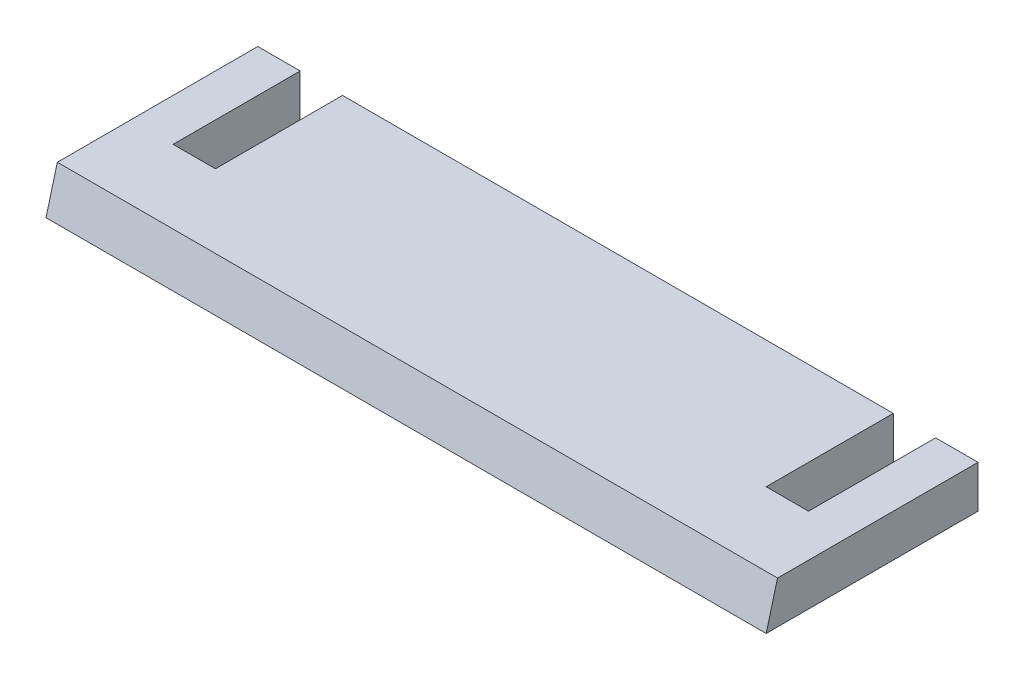
SolidWorks part; units mm, degrees
ref_plane "Front Plane" through (0, 0, 0) normal (0, 0, 1) x (1, 0, 0)
ref_plane "Top Plane" through (0, 0, 0) normal (0, 1, 0) x (1, 0, 0)
ref_plane "Right Plane" through (0, 0, 0) normal (1, 0, 0) x (0, 0, -1)
sketch "Sketch1" plane through (0, 0, 0) normal (0, 1, 0) x (1, 0, 0)
  line L0 (-75, 25) -> (-75, -5)
  line L1 (-85, -25) -> (85, -25)
  line L2 (-85, -25) -> (-85, 25)
  line L3 (-85, 25) -> (-75, 25)
  line L4 (85, -25) -> (85, 25)
  line L5 (-85, -25) -> (85, 25) construction
  line L6 (-85, 25) -> (85, -25) construction
  line L7 (-75, -5) -> (-65, -5)
  line L8 (-65, -5) -> (-65, 25)
  line L9 (0, 0) -> (0, 25) construction
  line L10 (75, -5) -> (65, -5)
  line L11 (75, 25) -> (75, -5)
  line L12 (65, -5) -> (65, 25)
  line L13 (-65, 25) -> (65, 25)
  line L14 (75, 25) -> (85, 25)
  point P0 (0, 0)
  point P8 (-75, 10)
  dimension "D1" = 170
  dimension "D2" = 50
  dimension "D3" = 10
  dimension "D4" = 30
  dimension "D5" = 10
extrude "Boss-Extrude1" add sketch "Sketch1" along normal blind 10
draft "Draft1" type of draft neutral plane draft angle 15 faces to draft 1 face at (0, 5, 25) neutral plane through (0, 0, 0) neutral plane normal (0, -1, 0) reverse direction yes parameters "D1"=15
